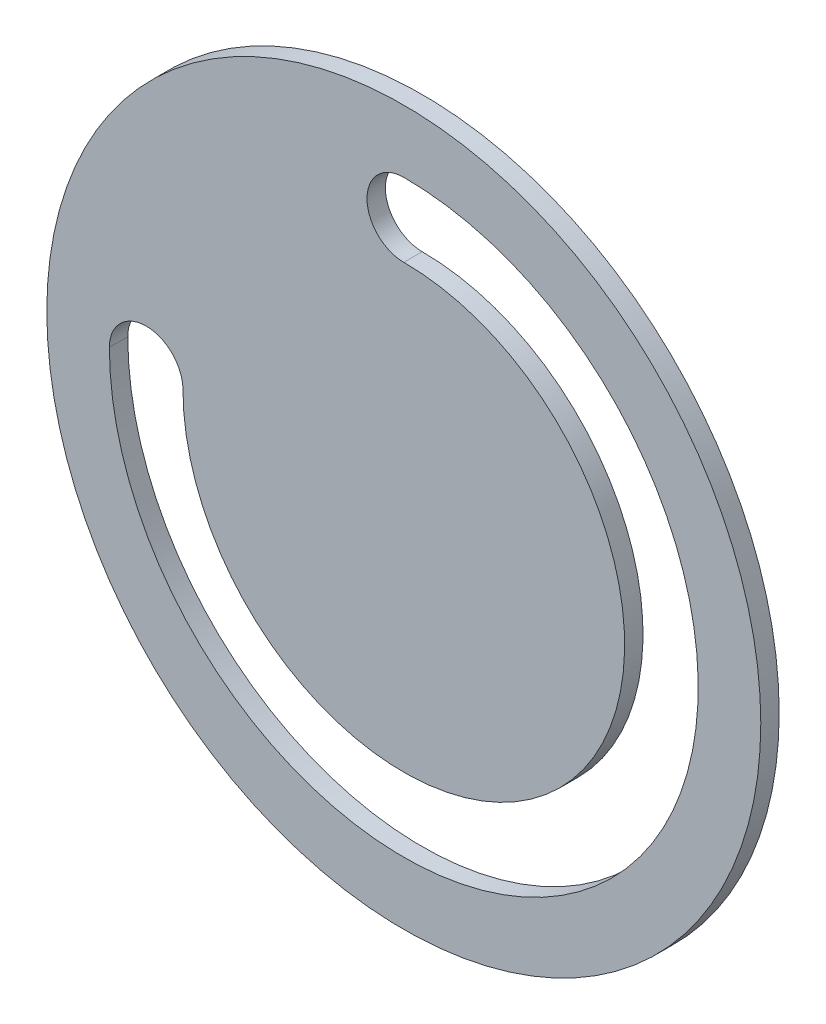
SolidWorks part; units mm, degrees
ref_plane "前视基准面" through (0, 0, 0) normal (0, 0, 1) x (1, 0, 0)
ref_plane "上视基准面" through (0, 0, 0) normal (0, 1, 0) x (1, 0, 0)
ref_plane "右视基准面" through (0, 0, 0) normal (1, 0, 0) x (0, 0, -1)
other "Configuration Table"
sketch "草图1" plane through (0, 0, 0) normal (0, 0, 1) x (1, 0, 0)
  circle A1 centre (0, 0) radius 9.7
  dimension "D1" = 19.4
extrude "凸台-拉伸1" add sketch "草图1" along normal blind 0.5
sketch "草图3" plane through (0, 0, 0.5) normal (0, 0, 1) x (1, 0, 0)
  line L0 (0, 0) -> (0, 7) construction
  line L1 (0, 0) -> (-7, 0) construction
  arc A0 (0, 7) -> (-7, 0) centre (0, 0) cw construction
  arc A1 (-8, 0) -> (0, 8) centre (0, 0) ccw
  arc A2 (-6, 0) -> (0, 6) centre (0, 0) ccw
  arc A3 (-6, 0) -> (-8, 0) centre (-7, 0) ccw
  arc A4 (0, 8) -> (0, 6) centre (0, 7) ccw
  point P3 (4.9497, -4.9497)
  dimension "D1" = 7
  dimension "D2" = 1
extrude "切除-拉伸1" cut sketch "草图3" against normal through all
